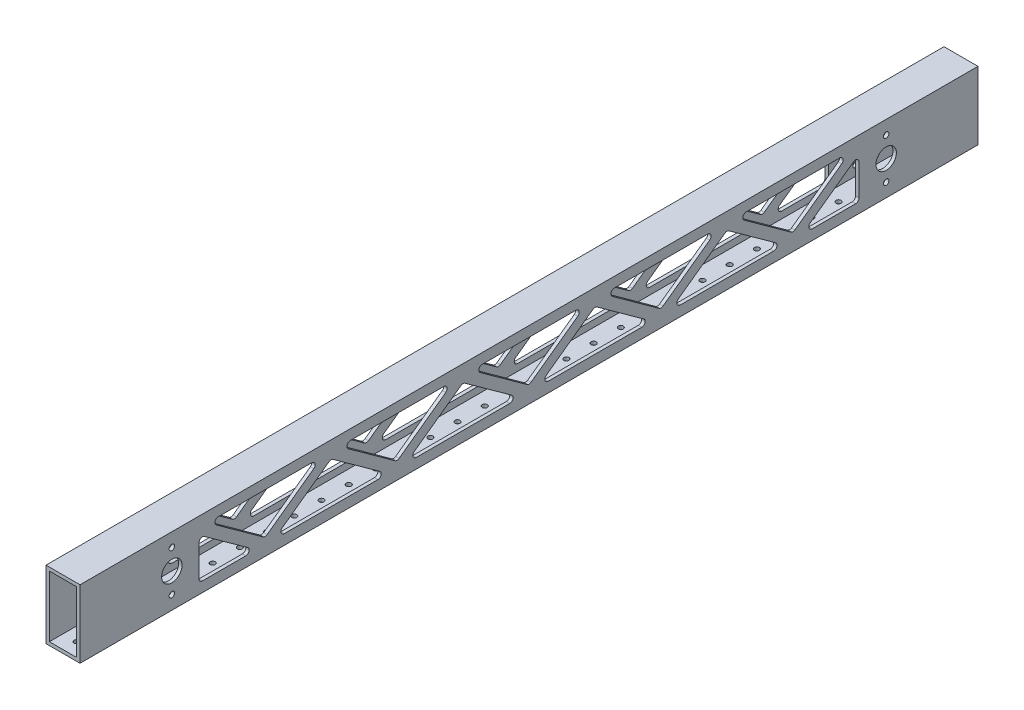
SolidWorks part; units mm, degrees
ref_plane "Front Plane" through (0, 0, 0) normal (0, 0, 1) x (1, 0, 0)
ref_plane "Top Plane" through (0, 0, 0) normal (0, 1, 0) x (1, 0, 0)
ref_plane "Right Plane" through (0, 0, 0) normal (1, 0, 0) x (0, 0, -1)
sketch "Sketch1" plane through (0, 0, 0) normal (0, 0, 1) x (1, 0, 0)
  line L1 (-12.1647, 2.5103) -> (19.5853, 2.5103)
  line L2 (-12.1647, 2.5103) -> (-12.1647, -60.9897)
  line L3 (-12.1647, -60.9897) -> (19.5853, -60.9897)
  line L4 (19.5853, 2.5103) -> (19.5853, -60.9897)
  line L5 (-8.9897, -0.6647) -> (16.4103, -0.6647)
  line L6 (-8.9897, -0.6647) -> (-8.9897, -57.8147)
  line L7 (-8.9897, -57.8147) -> (16.4103, -57.8147)
  line L8 (16.4103, -0.6647) -> (16.4103, -57.8147)
  dimension "D1" = 63.5
  dimension "D2" = 31.75
  dimension "D3" = 3.175
  dimension "D4" = 3.175
  dimension "D5" = 3.175
  dimension "D6" = 3.175
extrude "Boss-Extrude1" add sketch "Sketch1" along normal blind 838.2
sketch "Sketch2" plane through (19.5853, 0, 0) normal (1, 0, 0) x (0, 0, -1)
  line L0 (-838.2, 2.5103) -> (0, 2.5103) construction
  line L2 (-838.2, -60.9897) -> (-838.2, 2.5103) construction
  line L3 (-838.2, -60.9897) -> (0, -60.9897) construction
  line L4 (-419.1, 2.5103) -> (-419.1, -60.9897)
  circle A0 centre (-752.475, -29.2397) radius 9.525
  circle A1 centre (-752.475, -48.2897) radius 2.54
  circle A2 centre (-752.475, -10.1897) radius 2.54
  circle A3 centre (-85.725, -48.2897) radius 2.54
  circle A4 centre (-85.725, -29.2397) radius 9.525
  circle A5 centre (-85.725, -10.1897) radius 2.54
  dimension "D1" = 19.05
  dimension "D8" = 5.08
  dimension "D9" = 5.08
  dimension "D2" = 31.75
  dimension "D3" = 85.725
  dimension "D4" = 0
  dimension "D5" = 0
  dimension "D6" = 12.7
  dimension "D7" = 12.7
  dimension "D10" = 419.1
extrude "Cut-Extrude1" cut sketch "Sketch2" against normal up to surface (31.75 mm away) contours A0 | A2 | A1 | A5 | A4 | A3 up to face at (-12.1647, -29.2397, 419.1)
sketch "Sketch3" plane through (19.5853, 0, 0) normal (1, 0, 0) x (0, 0, -1)
  line L0 (-838.2, 2.5103) -> (0, 2.5103) construction
  line L1 (-736.6, 2.5103) -> (-101.6, 2.5103) construction
  line L2 (-736.6, 2.5103) -> (-736.6, -60.9897) construction
  line L3 (-736.6, -60.9897) -> (-101.6, -60.9897) construction
  line L4 (-101.6, 2.5103) -> (-101.6, -60.9897) construction
  line L5 (-838.2, -60.9897) -> (0, -60.9897) construction
  line L6 (-709.1113, -7.0147) -> (-621.8487, -7.0147)
  line L7 (-111.125, -19.0944) -> (-111.125, -48.2897)
  line L8 (-723.9, -51.4647) -> (-683.4437, -51.4647)
  line L9 (-727.075, -19.0944) -> (-727.075, -48.2897)
  line L10 (-727.075, -7.0147) -> (-665.48, -51.4647) construction
  line L11 (-665.48, -51.4647) -> (-603.885, -7.0147) construction
  line L12 (-603.885, -7.0147) -> (-542.29, -51.4647) construction
  line L13 (-542.29, -51.4647) -> (-480.695, -7.0147) construction
  line L14 (-480.695, -7.0147) -> (-419.1, -51.4647) construction
  line L15 (-419.1, -51.4647) -> (-357.505, -7.0147) construction
  line L16 (-357.505, -7.0147) -> (-295.91, -51.4647) construction
  line L17 (-295.91, -51.4647) -> (-234.315, -7.0147) construction
  line L18 (-234.315, -7.0147) -> (-172.72, -51.4647) construction
  line L19 (-172.72, -51.4647) -> (-111.125, -7.0147) construction
  line L20 (-722.042, -16.5198) -> (-681.5858, -45.7151)
  line L21 (-649.3742, -45.7151) -> (-605.743, -14.2286)
  line L22 (-602.027, -14.2286) -> (-558.3958, -45.7151)
  line L23 (-526.1842, -45.7151) -> (-482.553, -14.2286)
  line L24 (-478.837, -14.2286) -> (-435.2058, -45.7151)
  line L25 (-402.9942, -45.7151) -> (-359.363, -14.2286)
  line L26 (-355.647, -14.2286) -> (-312.0158, -45.7151)
  line L27 (-279.8042, -45.7151) -> (-236.173, -14.2286)
  line L28 (-232.457, -14.2286) -> (-188.8258, -45.7151)
  line L29 (-156.6142, -45.7151) -> (-116.158, -16.5198)
  line L30 (-710.9692, -12.7643) -> (-667.338, -44.2508)
  line L31 (-663.622, -44.2508) -> (-619.9908, -12.7643)
  line L32 (-587.7792, -12.7643) -> (-544.148, -44.2508)
  line L33 (-540.432, -44.2508) -> (-496.8008, -12.7643)
  line L34 (-464.5892, -12.7643) -> (-420.958, -44.2508)
  line L35 (-417.242, -44.2508) -> (-373.6108, -12.7643)
  line L36 (-341.3992, -12.7643) -> (-297.768, -44.2508)
  line L37 (-294.052, -44.2508) -> (-250.4208, -12.7643)
  line L38 (-218.2092, -12.7643) -> (-174.578, -44.2508)
  line L39 (-170.862, -44.2508) -> (-127.2308, -12.7643)
  line L40 (-729.8619, -10.8766) -> (-665.48, -57.3378) construction
  line L41 (-724.2881, -3.1528) -> (-665.48, -45.5916) construction
  line L42 (-665.48, -45.5916) -> (-603.885, -1.1416) construction
  line L43 (-603.885, -1.1416) -> (-542.29, -45.5916) construction
  line L44 (-542.29, -45.5916) -> (-480.695, -1.1416) construction
  line L45 (-480.695, -1.1416) -> (-419.1, -45.5916) construction
  line L46 (-419.1, -45.5916) -> (-357.505, -1.1416) construction
  line L47 (-357.505, -1.1416) -> (-295.91, -45.5916) construction
  line L48 (-295.91, -45.5916) -> (-234.315, -1.1416) construction
  line L49 (-234.315, -1.1416) -> (-172.72, -45.5916) construction
  line L50 (-172.72, -45.5916) -> (-113.9119, -3.1528) construction
  line L51 (-172.72, -57.3378) -> (-108.3381, -10.8766) construction
  line L52 (-234.315, -12.8878) -> (-172.72, -57.3378) construction
  line L53 (-357.505, -12.8878) -> (-295.91, -57.3378) construction
  line L54 (-295.91, -57.3378) -> (-234.315, -12.8878) construction
  line L55 (-480.695, -12.8878) -> (-419.1, -57.3378) construction
  line L56 (-419.1, -57.3378) -> (-357.505, -12.8878) construction
  line L57 (-542.29, -57.3378) -> (-480.695, -12.8878) construction
  line L58 (-603.885, -12.8878) -> (-542.29, -57.3378) construction
  line L59 (-665.48, -57.3378) -> (-603.885, -12.8878) construction
  line L60 (-727.075, -7.0147) -> (-111.125, -7.0147) construction
  line L61 (-727.075, -51.4647) -> (-111.125, -51.4647) construction
  line L62 (-727.075, -7.0147) -> (-727.075, -51.4647) construction
  line L63 (-647.5163, -51.4647) -> (-560.2537, -51.4647)
  line L64 (-585.9213, -7.0147) -> (-498.6587, -7.0147)
  line L65 (-524.3263, -51.4647) -> (-437.0637, -51.4647)
  line L66 (-462.7313, -7.0147) -> (-375.4687, -7.0147)
  line L67 (-401.1363, -51.4647) -> (-313.8737, -51.4647)
  line L68 (-339.5413, -7.0147) -> (-252.2787, -7.0147)
  line L69 (-277.9463, -51.4647) -> (-190.6837, -51.4647)
  line L70 (-216.3513, -7.0147) -> (-129.0887, -7.0147)
  line L71 (-154.7563, -51.4647) -> (-114.3, -51.4647)
  line L72 (-111.125, -7.0147) -> (-111.125, -51.4647) construction
  circle A0 centre (-752.475, -29.2397) radius 9.525 construction
  circle A1 centre (-85.725, -29.2397) radius 9.525 construction
  arc A2 (-602.027, -14.2286) -> (-605.743, -14.2286) centre (-603.885, -16.8032) ccw
  arc A3 (-621.8487, -7.0147) -> (-619.9908, -12.7643) centre (-621.8487, -10.1897) cw
  arc A4 (-709.1113, -7.0147) -> (-710.9692, -12.7643) centre (-709.1113, -10.1897) ccw
  arc A5 (-663.622, -44.2508) -> (-667.338, -44.2508) centre (-665.48, -41.6762) cw
  arc A6 (-683.4437, -51.4647) -> (-681.5858, -45.7151) centre (-683.4437, -48.2897) ccw
  arc A7 (-722.042, -16.5198) -> (-727.075, -19.0944) centre (-723.9, -19.0944) ccw
  arc A8 (-723.9, -51.4647) -> (-727.075, -48.2897) centre (-723.9, -48.2897) cw
  arc A9 (-114.3, -51.4647) -> (-111.125, -48.2897) centre (-114.3, -48.2897) ccw
  arc A10 (-111.125, -19.0944) -> (-116.158, -16.5198) centre (-114.3, -19.0944) ccw
  arc A11 (-154.7563, -51.4647) -> (-156.6142, -45.7151) centre (-154.7563, -48.2897) cw
  arc A12 (-174.578, -44.2508) -> (-170.862, -44.2508) centre (-172.72, -41.6762) ccw
  arc A13 (-127.2308, -12.7643) -> (-129.0887, -7.0147) centre (-129.0887, -10.1897) ccw
  arc A14 (-216.3513, -7.0147) -> (-218.2092, -12.7643) centre (-216.3513, -10.1897) ccw
  arc A15 (-279.8042, -45.7151) -> (-277.9463, -51.4647) centre (-277.9463, -48.2897) ccw
  arc A16 (-190.6837, -51.4647) -> (-188.8258, -45.7151) centre (-190.6837, -48.2897) ccw
  arc A17 (-232.457, -14.2286) -> (-236.173, -14.2286) centre (-234.315, -16.8032) ccw
  arc A18 (-252.2787, -7.0147) -> (-250.4208, -12.7643) centre (-252.2787, -10.1897) cw
  arc A19 (-294.052, -44.2508) -> (-297.768, -44.2508) centre (-295.91, -41.6762) cw
  arc A20 (-341.3992, -12.7643) -> (-339.5413, -7.0147) centre (-339.5413, -10.1897) cw
  arc A21 (-355.647, -14.2286) -> (-359.363, -14.2286) centre (-357.505, -16.8032) ccw
  arc A22 (-313.8737, -51.4647) -> (-312.0158, -45.7151) centre (-313.8737, -48.2897) ccw
  arc A23 (-401.1363, -51.4647) -> (-402.9942, -45.7151) centre (-401.1363, -48.2897) cw
  arc A24 (-373.6108, -12.7643) -> (-375.4687, -7.0147) centre (-375.4687, -10.1897) ccw
  arc A25 (-417.242, -44.2508) -> (-420.958, -44.2508) centre (-419.1, -41.6762) cw
  arc A26 (-462.7313, -7.0147) -> (-464.5892, -12.7643) centre (-462.7313, -10.1897) ccw
  arc A27 (-437.0637, -51.4647) -> (-435.2058, -45.7151) centre (-437.0637, -48.2897) ccw
  arc A28 (-478.837, -14.2286) -> (-482.553, -14.2286) centre (-480.695, -16.8032) ccw
  arc A29 (-524.3263, -51.4647) -> (-526.1842, -45.7151) centre (-524.3263, -48.2897) cw
  arc A30 (-587.7792, -12.7643) -> (-585.9213, -7.0147) centre (-585.9213, -10.1897) cw
  arc A31 (-498.6587, -7.0147) -> (-496.8008, -12.7643) centre (-498.6587, -10.1897) cw
  arc A32 (-540.432, -44.2508) -> (-544.148, -44.2508) centre (-542.29, -41.6762) cw
  arc A33 (-560.2537, -51.4647) -> (-558.3958, -45.7151) centre (-560.2537, -48.2897) ccw
  arc A34 (-649.3742, -45.7151) -> (-647.5163, -51.4647) centre (-647.5163, -48.2897) ccw
  point P93 (-164.5816, -51.4647)
  point P99 (-119.2634, -7.0147)
  point P102 (-226.1766, -7.0147)
  point P105 (-287.7716, -51.4647)
  point P108 (-180.8584, -51.4647)
  point P114 (-242.4534, -7.0147)
  point P120 (-349.3666, -7.0147)
  point P126 (-304.0484, -51.4647)
  point P129 (-410.9616, -51.4647)
  point P132 (-365.6434, -7.0147)
  point P138 (-472.5566, -7.0147)
  point P141 (-427.2384, -51.4647)
  point P147 (-534.1516, -51.4647)
  point P150 (-595.7466, -7.0147)
  point P153 (-488.8334, -7.0147)
  point P159 (-550.4284, -51.4647)
  point P162 (-657.3416, -51.4647)
  dimension "D6" = 3.175
  dimension "D7" = 3.175
  dimension "D1" = 15.875
  dimension "D2" = 15.875
  dimension "D3" = 9.525
  dimension "D4" = 4.7625
  dimension "D5" = 4.7625
extrude "Cut-Extrude2" cut sketch "Sketch3" against normal through all contours L20 L9 L8 | L30 L31 L6 | L22 L21 L8 | L32 L33 L6 | L24 L23 L8 | L34 L35 L6 | L26 L25 L8 | L36 L37 L6 | L28 L27 L8 | L38 L39 L6 | L29 L8 L7
sketch "Sketch4" plane through (0, -60.9897, 0) normal (0, -1, 0) x (1, 0, 0)
  line L0 (-12.1647, 838.2) -> (19.5853, 838.2) construction
  line L1 (19.5853, 838.2) -> (19.5853, 0) construction
  circle A0 centre (3.7103, 825.5) radius 2.3813
  circle A1 centre (3.7103, 800.1) radius 2.3813
  circle A2 centre (3.7103, 774.7) radius 2.3813
  circle A3 centre (3.7103, 749.3) radius 2.3813
  circle A4 centre (3.7103, 723.9) radius 2.3813
  circle A5 centre (3.7103, 698.5) radius 2.3813
  circle A6 centre (3.7103, 673.1) radius 2.3813
  circle A7 centre (3.7103, 647.7) radius 2.3813
  circle A8 centre (3.7103, 622.3) radius 2.3813
  circle A9 centre (3.7103, 596.9) radius 2.3813
  circle A10 centre (3.7103, 571.5) radius 2.3813
  circle A11 centre (3.7103, 546.1) radius 2.3813
  circle A12 centre (3.7103, 520.7) radius 2.3813
  circle A13 centre (3.7103, 495.3) radius 2.3813
  circle A14 centre (3.7103, 469.9) radius 2.3813
  circle A15 centre (3.7103, 444.5) radius 2.3813
  circle A16 centre (3.7103, 419.1) radius 2.3813
  circle A17 centre (3.7103, 393.7) radius 2.3813
  circle A18 centre (3.7103, 368.3) radius 2.3813
  circle A19 centre (3.7103, 342.9) radius 2.3813
  circle A20 centre (3.7103, 317.5) radius 2.3813
  circle A21 centre (3.7103, 292.1) radius 2.3813
  circle A22 centre (3.7103, 266.7) radius 2.3813
  circle A23 centre (3.7103, 241.3) radius 2.3813
  circle A24 centre (3.7103, 215.9) radius 2.3813
  circle A25 centre (3.7103, 190.5) radius 2.3813
  circle A26 centre (3.7103, 165.1) radius 2.3813
  circle A27 centre (3.7103, 139.7) radius 2.3813
  circle A28 centre (3.7103, 114.3) radius 2.3813
  circle A29 centre (3.7103, 88.9) radius 2.3813
  circle A30 centre (3.7103, 63.5) radius 2.3813
  circle A31 centre (3.7103, 38.1) radius 2.3813
  circle A32 centre (3.7103, 12.7) radius 2.3813
  dimension "D1" = 4.7625
  dimension "D2" = 12.7
  dimension "D3" = 15.875
  dimension "D4" = 33
extrude "Cut-Extrude3" cut sketch "Sketch4" against normal blind 3.175
